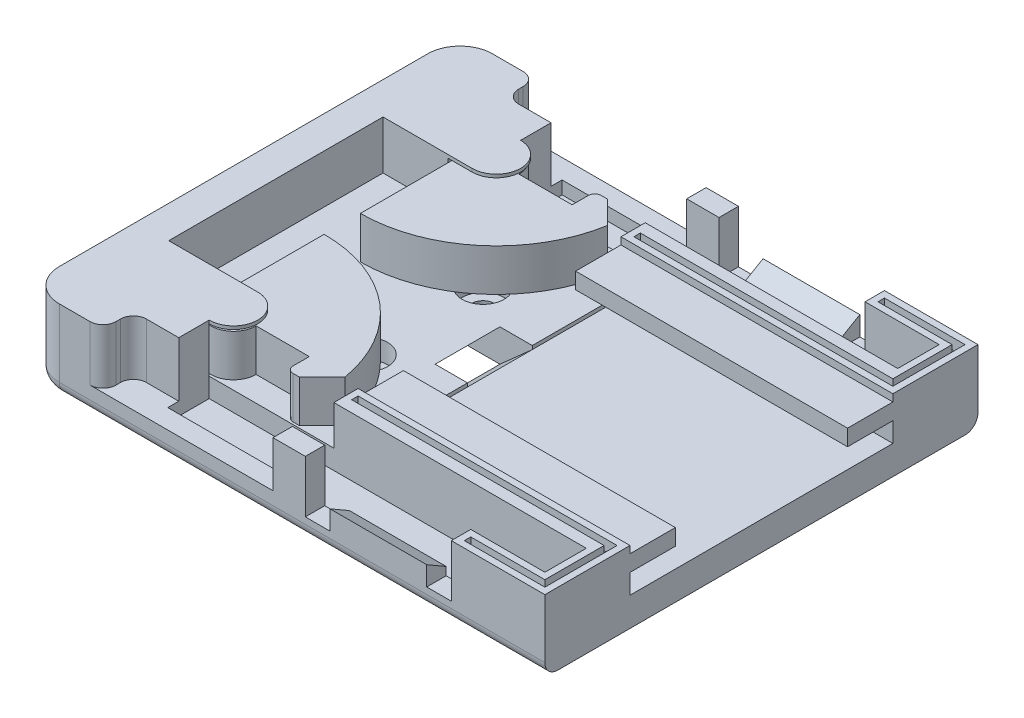
SolidWorks part; units mm, degrees
ref_plane "Front Plane" through (0, 0, 0) normal (0, 0, 1) x (1, 0, 0)
ref_plane "Top Plane" through (0, 0, 0) normal (0, 1, 0) x (1, 0, 0)
ref_plane "Right Plane" through (0, 0, 0) normal (1, 0, 0) x (0, 0, -1)
sketch "Sketch1" plane through (0, 0, 0) normal (0, 1, 0) x (1, 0, 0)
  line L0 (5, 33.45) -> (5, 16.9)
  line L1 (0, 0) -> (80, 0)
  line L2 (0, 0) -> (0, 33.45)
  line L3 (0, 33.45) -> (80, 33.45)
  line L4 (80, 0) -> (80, 33.45)
  line L5 (5, 16.9) -> (15, 16.9)
  line L6 (15, 16.9) -> (15, 13.15)
  line L7 (18.75, 9.4) -> (18.75, 3)
  line L8 (18.75, 3) -> (77, 3)
  line L10 (18.75, 9.4) -> (77, 9.4)
  line L11 (77, 3) -> (77, 9.4)
  line L12 (38, 9.4) -> (80, 9.4)
  line L13 (38, 9.4) -> (38, 13.15)
  line L14 (38, 13.15) -> (80, 13.15)
  line L15 (80, 9.4) -> (80, 13.15)
  circle A0 centre (18.75, 13.15) radius 2.25
  arc A1 (15, 13.15) -> (18.75, 9.4) centre (18.75, 13.15) ccw
  circle A2 centre (18.75, 13.15) radius 3.75 construction
  point P12 (10, 16.9)
  dimension "D11" = 1.5
  dimension "D12" = 4.5
  dimension "D1" = 33.45
  dimension "D2" = 80
  dimension "D3" = 3
  dimension "D4" = 3
  dimension "D5" = 7.5
  dimension "D6" = 6.4
  dimension "D7" = 5
  dimension "D8" = 10
  dimension "D9" = 3.75
  dimension "D10" = 42
extrude "Boss-Extrude1" add sketch "Sketch1" along normal blind 7.5 contours A1 L6 L5 L0 L3 L2 L1 L4 L12 L11 L8 L7 | A0 | L14 L13 L10 L12 L4
sketch "Sketch2" plane through (0, 0, 0) normal (0, -1, 0) x (-1, 0, 0)
  line L1 (0, 0) -> (-80, 0)
  line L2 (0, 0) -> (0, 33.45)
  line L3 (0, 33.45) -> (-80, 33.45)
  line L4 (-80, 0) -> (-80, 33.45)
extrude "Boss-Extrude2" add sketch "Sketch2" along normal blind 5
sketch "Sketch3" plane through (0, 0, 0) normal (0, 0, 1) x (1, 0, 0)
  line L0 (0, 7.5) -> (80, 7.5) construction
  line L1 (63, 6.1) -> (43, 6.1)
  line L3 (63, 1.5) -> (43, 1.5)
  line L4 (43, 6.1) -> (43, 1.5)
  line L5 (38, 7.5) -> (38, 0)
  line L6 (80, -5) -> (80, 7.5) construction
  line L7 (63, 6.1) -> (63, 1.5)
  line L8 (43, 1.5) -> (46.8, 1.5)
  line L9 (43, 1.5) -> (43, -2)
  line L10 (43, -2) -> (46.8, -2)
  line L11 (46.8, 1.5) -> (46.8, -2)
  line L12 (38, 0) -> (18.75, 0)
  line L13 (38, 0) -> (38, 7.5)
  line L14 (38, 7.5) -> (18.75, 7.5)
  line L15 (18.75, 0) -> (18.75, 7.5)
  line L20 (63, 1.5) -> (65.55, 1.5)
  line L21 (46.8, -2) -> (47.1, 1.5)
  line L22 (47.1, 1.5) -> (46.8, 1.5)
  line L23 (65.55, 1.5) -> (65.55, 6.1)
  line L24 (65.55, 6.1) -> (63, 6.1)
  line L25 (80, -5) -> (0, -5) construction
  line L26 (65.55, 1.5) -> (61.75, 1.5)
  line L27 (65.55, 1.5) -> (65.55, -2)
  line L28 (65.55, -2) -> (61.75, -2)
  line L29 (61.75, 1.5) -> (61.75, -2)
  dimension "D1" = 4.6
  dimension "D2" = 3
  dimension "D3" = 20
  dimension "D4" = 7.5
  dimension "D5" = 5
  dimension "D6" = 42
  dimension "D7" = 3.8
  dimension "D8" = 19.25
  dimension "D9" = 3.5
  dimension "D10" = 14.45
  dimension "D11" = 3.8
  dimension "D12" = 3.5
  dimension "D13" = 0.3
extrude "Cut-Extrude1" cut sketch "Sketch3" against normal blind 3
sketch "Sketch4" plane through (0, 0, 0) normal (0, 1, 0) x (1, 0, 0)
  line L1 (18.75, 9.4) -> (77, 9.4)
  line L2 (18.75, 9.4) -> (18.75, 3)
  line L3 (18.75, 3) -> (77, 3)
  line L4 (77, 9.4) -> (77, 3)
extrude "Cut-Extrude2" cut sketch "Sketch4" against normal blind 3
sketch "Sketch5" plane through (80, 0, 0) normal (1, 0, 0) x (0, 0, -1)
  line L0 (13.15, 7.5) -> (13.15, 0) construction
  line L1 (13.15, 5) -> (20.15, 5)
  line L2 (13.15, 5) -> (13.15, 2.5)
  line L3 (13.15, 2.5) -> (20.15, 2.5)
  line L4 (20.15, 5) -> (20.15, 2.5)
  line L5 (0, 7.5) -> (13.15, 7.5) construction
  dimension "D1" = 2.5
  dimension "D2" = 2.5
  dimension "D3" = 7
extrude "Boss-Extrude3" add sketch "Sketch5" against normal up to surface (42 mm away) up to face at (38, 3.75, -11.275)
sketch "Sketch6" plane through (0, 0, 0) normal (0, 1, 0) x (1, 0, 0)
  line L0 (38, 13.15) -> (80, 13.15) construction
  line L1 (80, 33.45) -> (39.6, 33.45)
  line L2 (80, 33.45) -> (80, 13.15)
  line L3 (80, 13.15) -> (39.6, 13.15)
  line L4 (39.6, 33.45) -> (39.6, 13.15)
  dimension "D1" = 40.4
extrude "Cut-Extrude3" cut sketch "Sketch6" against normal blind 0.55
sketch "Sketch7" plane through (0, 0, 0) normal (0, 1, 0) x (1, 0, 0)
  line L0 (15.25, 13.15) -> (15.25, 9.65)
  line L1 (15.25, 9.65) -> (18.75, 9.65)
  line L2 (15.25, 9.65) -> (36.25, 9.65)
  line L3 (15.25, 9.65) -> (15.25, 30.65)
  line L4 (22.25, 13.15) -> (35.9563, 13.15)
  line L5 (35.9563, 13.15) -> (32.4563, 9.65)
  line L6 (30.4563, 9.65) -> (26.9563, 13.15)
  line L7 (30.4563, 9.65) -> (30.4563, 13.15)
  circle A0 centre (18.75, 13.15) radius 2.6
  circle A1 centre (18.75, 13.15) radius 3.5
  circle A2 centre (15.25, 9.65) radius 21
  dimension "D1" = 5.2
  dimension "D2" = 7
  dimension "D4" = 42
  dimension "D3" = 3.5
  dimension "D5" = 2
  dimension "D6" = 45
extrude "Boss-Extrude4" add sketch "Sketch7" along normal blind 6.5 from offset 0.1 separate body contours L4 A2 L3 A1 | L6 L2 L5 L4 | A1 A0
sketch "Sketch8" plane through (0, 7.5, 0) normal (0, 1, 0) x (1, 0, 0)
  line L0 (15, 16.9) -> (15, 13.15)
  line L1 (15, 16.9) -> (18.75, 16.9)
  arc A0 (15, 13.15) -> (18.75, 16.9) centre (18.75, 13.15) ccw
extrude "Boss-Extrude5" add sketch "Sketch8" against normal blind 0.5
sketch "Sketch9" plane through (0, 7.5, 0) normal (0, 1, 0) x (1, 0, 0)
  line L0 (18.75, 9.4) -> (18.75, 0) construction
  line L1 (18.75, 4.7) -> (11.75, 4.7)
  line L2 (18.75, 4.7) -> (18.75, 0)
  line L3 (18.75, 0) -> (11.75, 0)
  line L4 (11.75, 4.7) -> (11.75, 0)
  line L5 (0, 0) -> (18.75, 0) construction
  dimension "D1" = 7
extrude "Cut-Extrude4" cut sketch "Sketch9" against normal up to surface (7.5 mm away) up to face at (18.75, 0, -10.9)
sketch "Sketch10" plane through (0, 0, 0) normal (0, 1, 0) x (1, 0, 0)
  line L0 (18.75, 4.7) -> (18.75, 3)
  line L1 (18.75, 3) -> (38, 3)
  line L2 (38, 3) -> (38, 0)
  line L3 (38, 0) -> (11.75, 0)
  line L4 (11.75, 0) -> (11.75, 4.7)
  line L5 (11.75, 4.7) -> (18.75, 4.7)
extrude "Cut-Extrude5" cut sketch "Sketch10" against normal blind 1
fillet "Fillet2" radius 2 2 edges at (11.75, 3.25, 0) (11.75, 3.25, -4.7)
fillet "Fillet3" radius 1 1 edges at (30.4563, 3.35, -9.65)
fillet "Fillet4" radius 5 1 edges at (0, 1.25, 0)
fillet "Fillet5" radius 2 3 edges at (0, -5, -19.225) (1.4645, -5, -1.4645) (42.5, -5, 0)
sketch "Sketch15" plane through (0, 0, -33.45) normal (0, 0, -1) x (-1, 0, 0)
  line L0 (-39.6, 0) -> (-34.6, 0)
  line L1 (-5, 0) -> (-39.6, 0) construction
  line L2 (-34.6, 0) -> (-29.6, -5)
  line L3 (-2, -5) -> (-80, -5) construction
  line L4 (-29.6, -5) -> (-34.6, -5)
  line L5 (-34.6, -5) -> (-39.6, -0.55)
  line L6 (-39.6, -0.55) -> (-39.6, 0)
  dimension "D1" = 5
  dimension "D2" = 5
  dimension "D3" = 135
extrude "Cut-Extrude11" cut sketch "Sketch15" against normal blind 5
sketch "Sketch16" plane through (46.8, 0, 0) normal (-1, 0, 0) x (0, 0, 1)
  line L0 (-3, -0.75) -> (0, 0.9821)
  line L1 (-3, 1.5) -> (-3, -2) construction
  line L2 (0, 1.5) -> (0, -2) construction
  line L3 (0, 0.9821) -> (0, 1.5)
  line L4 (0, 1.5) -> (-3, 1.5)
  line L5 (-3, 1.5) -> (-3, -0.75)
  line L6 (-3, -2) -> (0, -2) construction
  line M3 (0, 1.5) -> (-3, 1.5)
  line M4 (-3, 1.5) -> (-3, -2)
  dimension "D1" = 1.25
  dimension "D2" = 30
extrude "Cut-Extrude12" cut sketch "Sketch16" against normal up to next (14.95 mm away) contours L0 M4 M3
sketch "Sketch17" plane through (0, 7.5, 0) normal (0, 1, 0) x (1, 0, 0)
  line L1 (80, 0) -> (38, 0)
  line L2 (80, 0) -> (80, 13.15)
  line L3 (80, 13.15) -> (38, 13.15)
  line L4 (38, 0) -> (38, 13.15)
extrude "Cut-Extrude13" cut sketch "Sketch17" against normal up to surface (1.4 mm away) up to face at (54.275, 6.1, -1.5)
sketch "Sketch18" plane through (0, 6.1, 0) normal (0, 1, 0) x (1, 0, 0)
  line L0 (38, 13.15) -> (80, 13.15)
  line L1 (80, 13.15) -> (80, 0)
  line L2 (80, 0) -> (65.55, 0)
  line L3 (65.55, 0) -> (65.55, 3)
  line L4 (65.55, 3) -> (77, 3)
  line L5 (77, 3) -> (77, 10.15)
  line L6 (77, 10.15) -> (38, 10.15)
  line L7 (38, 9.4) -> (38, 13.15) construction
  line L8 (38, 10.15) -> (38, 13.15)
  line L9 (39, 11.15) -> (39, 12.15)
  line L10 (39, 12.15) -> (79, 12.15)
  line L11 (79, 12.15) -> (79, 1)
  line L12 (79, 1) -> (66.55, 1)
  line L13 (66.55, 1) -> (66.55, 2)
  line L14 (66.55, 2) -> (78, 2)
  line L15 (78, 2) -> (78, 11.15)
  line L16 (78, 11.15) -> (39, 11.15)
  dimension "D1" = 3
  dimension "D2" = 1
extrude "Cut-Extrude14" cut sketch "Sketch18" against normal blind 1.7 contours L16 L15 L14 L13 L12 L11 L10 L9
mirror "Mirror1" about plane through (0, -5, -33.45) normal (0, 0, 1) of bodies 143
ref_plane "Plane14" through (0, 0, -33.45) normal (0, 0, 1) x (1, 0, 0)
mirror "Mirror2" about plane through (0, 0, -33.45) normal (0, 0, 1) of bodies 108
sketch "Sketch19" plane through (0, 0, 0) normal (0, 1, 0) x (1, 0, 0)
  line L0 (5, 33.45) -> (80, 33.45)
  line L1 (5, 50) -> (5, 16.9) construction
  line L2 (80, 13.15) -> (80, 53.75) construction
  line L3 (80, 33.45) -> (5.6792, 33.45) construction
  line L4 (28, 24.45) -> (28, 37.8306) construction
  circle A0 centre (28, 42.45) radius 3.25
  circle A1 centre (28, 24.45) radius 3.25
  circle A2 centre (13, 24.45) radius 3.25
  circle A3 centre (28, 24.45) radius 1.7
  circle A4 centre (28, 42.45) radius 1.7
  circle A5 centre (13, 24.45) radius 1.7
  dimension "D1" = 15
  dimension "D2" = 15
  dimension "D3" = 18
extrude "Cut-Extrude15" cut sketch "Sketch19" against normal blind 3 contours A1 A3 | A2 A5 | A5 | A3 | A4 | A0 A4
sketch "Sketch20" plane through (0, -3, 0) normal (0, 1, 0) x (1, 0, 0)
  circle A0 centre (13, 24.45) radius 1.7
  circle A1 centre (28, 24.45) radius 1.7
  circle A2 centre (28, 42.45) radius 1.7
  dimension "D1" = 3.4
extrude "Cut-Extrude16" cut sketch "Sketch20" against normal through all
